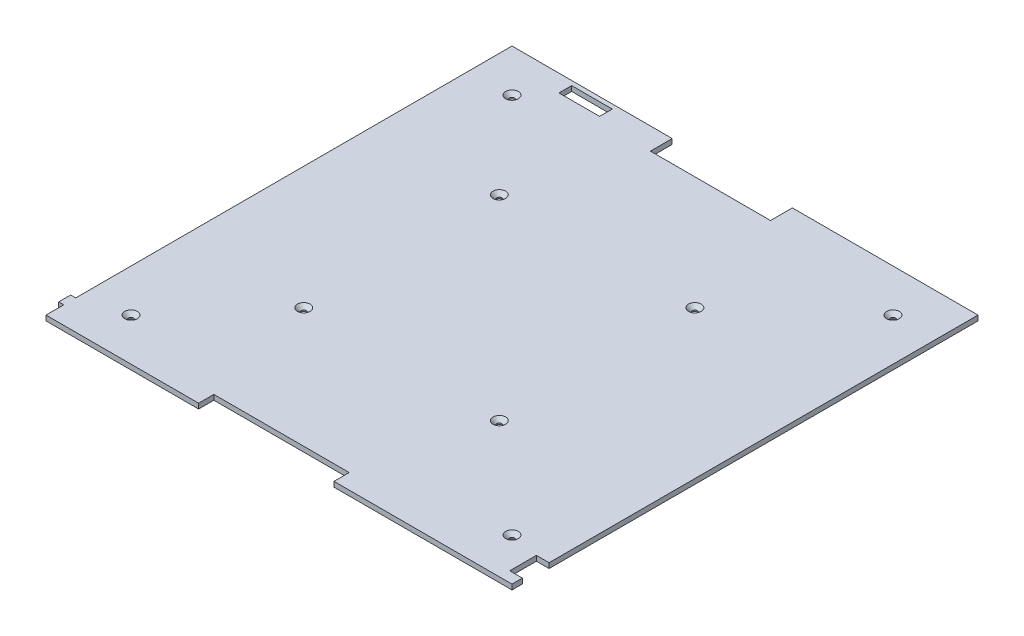
SolidWorks part; units mm, degrees
ref_plane "Front Plane" through (0, 0, 0) normal (0, 0, 1) x (1, 0, 0)
ref_plane "Top Plane" through (0, 0, 0) normal (0, 1, 0) x (1, 0, 0)
ref_plane "Right Plane" through (0, 0, 0) normal (1, 0, 0) x (0, 0, -1)
sketch "Sketch1" plane through (0, 0, 0) normal (0, 1, 0) x (1, 0, 0)
  line L0 (-92, 92) -> (-92, -79.8) construction
  line L1 (-28.4, 92) -> (-92, 92) construction
  line L2 (-28.4, 83.4) -> (-28.4, 92) construction
  line L3 (18.4, 83.4) -> (-28.4, 83.4) construction
  line L4 (18.4, 92) -> (18.4, 83.4) construction
  line L5 (92, 92) -> (18.4, 92) construction
  line L6 (92, -77.4) -> (92, 92) construction
  line L7 (87, -77.4) -> (92, -77.4) construction
  line L8 (87, -87.4) -> (87, -77.4) construction
  line L9 (92, -87.4) -> (87, -87.4) construction
  line L10 (92, -92) -> (92, -87.4) construction
  line L11 (21.4, -92) -> (92, -92) construction
  line L12 (21.4, -86) -> (21.4, -92) construction
  line L13 (-31.4, -86) -> (21.4, -86) construction
  line L14 (-31.4, -92) -> (-31.4, -86) construction
  line L15 (-92, -92) -> (-31.4, -92) construction
  line L16 (-92, -85) -> (-92, -92) construction
  line L17 (-94, -85) -> (-92, -85) construction
  line L18 (-94, -79.8) -> (-94, -85) construction
  line L19 (-92, -79.8) -> (-94, -79.8) construction
  line L20 (-91.75, 91.75) -> (-91.75, -80.05)
  line L21 (-91.75, -80.05) -> (-93.75, -80.05)
  line L22 (-93.75, -80.05) -> (-93.75, -84.75)
  line L23 (-93.75, -84.75) -> (-91.75, -84.75)
  line L24 (-91.75, -84.75) -> (-91.75, -91.75)
  line L25 (-91.75, -91.75) -> (-31.65, -91.75)
  line L26 (-31.65, -91.75) -> (-31.65, -85.75)
  line L27 (-31.65, -85.75) -> (21.65, -85.75)
  line L28 (21.65, -85.75) -> (21.65, -91.75)
  line L29 (21.65, -91.75) -> (91.75, -91.75)
  line L30 (91.75, -91.75) -> (91.75, -87.65)
  line L31 (91.75, -87.65) -> (86.75, -87.65)
  line L32 (86.75, -87.65) -> (86.75, -77.15)
  line L33 (86.75, -77.15) -> (91.75, -77.15)
  line L34 (91.75, -77.15) -> (91.75, 91.75)
  line L35 (91.75, 91.75) -> (18.65, 91.75)
  line L36 (18.65, 91.75) -> (18.65, 83.15)
  line L37 (18.65, 83.15) -> (-28.65, 83.15)
  line L38 (-28.65, 83.15) -> (-28.65, 91.75)
  line L39 (-28.65, 91.75) -> (-91.75, 91.75)
  dimension "D1" = 184
  dimension "D2" = 184
  dimension "D3" = 8.6
  dimension "D4" = 63.6
  dimension "D5" = 46.8
  dimension "D6" = 2
  dimension "D7" = 7
  dimension "D8" = 5.2
  dimension "D9" = 4.6
  dimension "D10" = 10
  dimension "D11" = 70.6
  dimension "D12" = 52.8
  dimension "D13" = 5
  dimension "D14" = 6
  dimension "D15" = 92
  dimension "D16" = 92
  dimension "D17" = 0.25
extrude "Boss-Extrude1" add sketch "Sketch1" along normal blind 2
sketch "Sketch2" plane through (0, 0, 0) normal (0, -1, 0) x (1, 0, 0)
  circle A0 centre (75, -75) radius 1
  circle A1 centre (-75, -75) radius 1
  circle A2 centre (-75, 75) radius 1
  circle A3 centre (75, 75) radius 1
  circle A4 centre (33.5, -38.5) radius 1
  circle A5 centre (33.5, 38.5) radius 1
  circle A6 centre (-43.5, -38.5) radius 1
  circle A7 centre (-43.5, 38.5) radius 1
  dimension "D1" = 2
  dimension "D2" = 2
  dimension "D3" = 2
  dimension "D4" = 2
  dimension "D5" = 2
  dimension "D6" = 2
  dimension "D7" = 2
  dimension "D8" = 2
extrude "Cut-Extrude1" cut sketch "Sketch2" against normal through all
chamfer "Chamfer1" distance 1.5 angle 45 8 edges at (75, 2, -76) (33.5, 2, -39.5) (75, 2, 74) (33.5, 2, 37.5) (-43.5, 2, 37.5) (-43.5, 2, -39.5) (-75, 2, -76) (-75, 2, 74)
sketch "Sketch3" plane through (0, 0, 0) normal (0, -1, 0) x (1, 0, 0)
  line L1 (-50.5, -90) -> (-66.5, -90)
  line L2 (-50.5, -90) -> (-50.5, -85)
  line L3 (-50.5, -85) -> (-66.5, -85)
  line L4 (-66.5, -90) -> (-66.5, -85)
extrude "Cut-Extrude2" cut sketch "Sketch3" against normal through all
